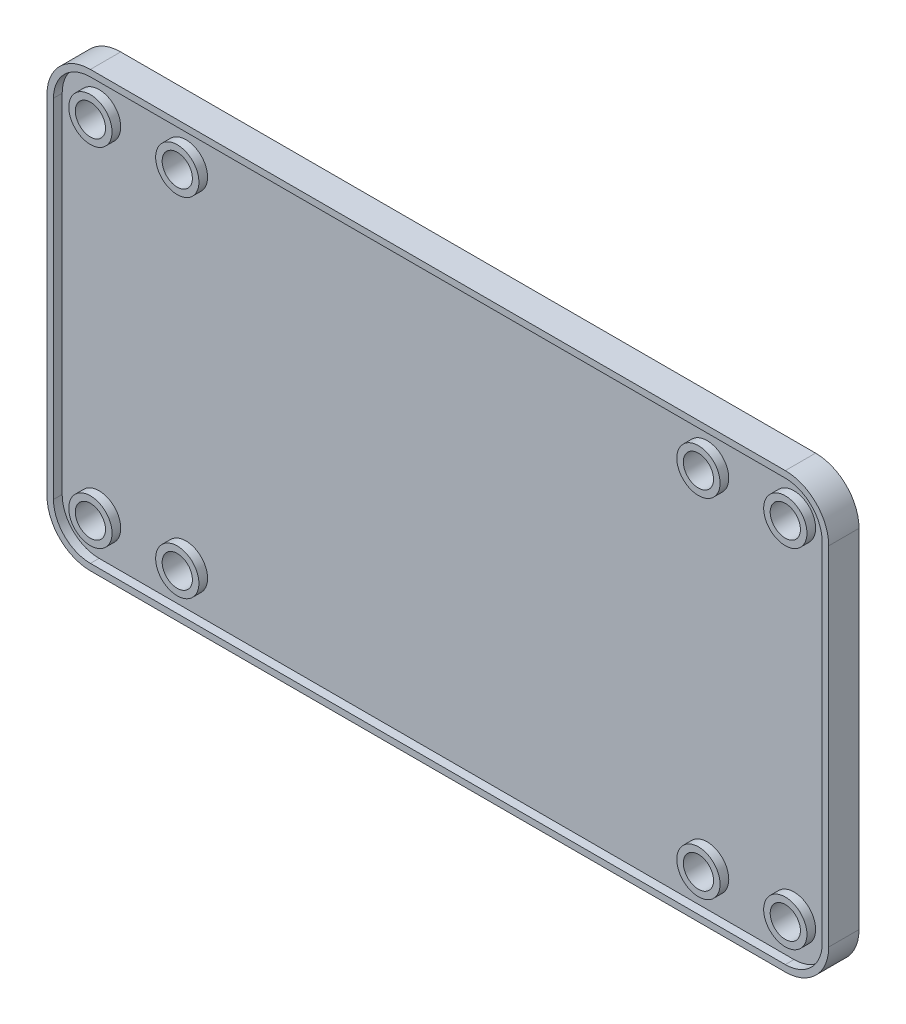
SolidWorks part; units mm, degrees
material "ABS"
ref_plane "Front Plane" through (0, 0, 0) normal (0, 0, 1) x (1, 0, 0)
ref_plane "Top Plane" through (0, 0, 0) normal (0, 1, 0) x (1, 0, 0)
ref_plane "Right Plane" through (0, 0, 0) normal (1, 0, 0) x (0, 0, -1)
sketch "Sketch1" plane through (0, 0, 0) normal (0, 0, 1) x (1, 0, 0)
  line L0 (-57.15, 0) -> (57.15, 0) construction
  line L1 (-50.8, -31.75) -> (50.8, -31.75)
  line L2 (-57.15, -25.4) -> (-57.15, 25.4)
  line L3 (-50.8, 31.75) -> (50.8, 31.75)
  line L4 (57.15, -25.4) -> (57.15, 25.4)
  line L5 (-57.15, -31.75) -> (57.15, 31.75) construction
  line L6 (-57.15, 31.75) -> (57.15, -31.75) construction
  line L7 (0, 31.75) -> (0, -31.75) construction
  arc A0 (50.8, 31.75) -> (57.15, 25.4) centre (50.8, 25.4) cw
  arc A1 (50.8, -31.75) -> (57.15, -25.4) centre (50.8, -25.4) ccw
  arc A2 (-50.8, -31.75) -> (-57.15, -25.4) centre (-50.8, -25.4) cw
  arc A3 (-57.15, 25.4) -> (-50.8, 31.75) centre (-50.8, 25.4) cw
  circle A4 centre (-50.8, -25.4) radius 2.2098
  circle A5 centre (-38.1, -25.4) radius 2.2098
  circle A6 centre (-50.8, 25.4) radius 2.2098
  circle A7 centre (-38.1, 25.4) radius 2.2098
  circle A8 centre (50.8, 25.4) radius 2.2098
  circle A9 centre (38.1, 25.4) radius 2.2098
  circle A10 centre (50.8, -25.4) radius 2.2098
  circle A11 centre (38.1, -25.4) radius 2.2098
  point P0 (0, 0)
  dimension "D3" = 6.35
  dimension "D4" = 4.4196
  dimension "D1" = 63.5
  dimension "D2" = 114.3
  dimension "D5" = 6.35
  dimension "D6" = 12.7
  dimension "D7" = 6.35
extrude "Boss-Extrude1" add sketch "Sketch1" against normal blind 3.175
sketch "Sketch2" plane through (0, 0, 0) normal (0, 0, 1) x (1, 0, 0)
  line L12 (50.8, 30.7975) -> (-50.8, 30.7975)
  line L13 (-56.1975, 25.4) -> (-56.1975, -25.4)
  line L14 (-50.8, -30.7975) -> (50.8, -30.7975)
  line L15 (56.1975, -25.4) -> (56.1975, 25.4)
  line L16 (50.8, 30.7975) -> (-50.8, 30.7975)
  line L17 (-56.1975, 25.4) -> (-56.1975, -25.4)
  line L18 (-50.8, -30.7975) -> (50.8, -30.7975)
  line L19 (56.1975, -25.4) -> (56.1975, 25.4)
  circle A0 centre (-50.8, -25.4) radius 2.2098 construction
  arc A8 (56.1975, 25.4) -> (50.8, 30.7975) centre (50.8, 25.4) ccw
  arc A9 (-50.8, 30.7975) -> (-56.1975, 25.4) centre (-50.8, 25.4) ccw
  arc A10 (-56.1975, -25.4) -> (-50.8, -30.7975) centre (-50.8, -25.4) ccw
  arc A11 (50.8, -30.7975) -> (56.1975, -25.4) centre (50.8, -25.4) ccw
  arc A12 (56.1975, 25.4) -> (50.8, 30.7975) centre (50.8, 25.4) ccw
  arc A13 (-50.8, 30.7975) -> (-56.1975, 25.4) centre (-50.8, 25.4) ccw
  arc A14 (-56.1975, -25.4) -> (-50.8, -30.7975) centre (-50.8, -25.4) ccw
  arc A15 (50.8, -30.7975) -> (56.1975, -25.4) centre (50.8, -25.4) ccw
  circle A36 centre (38.1, 25.4) radius 3.1623
  circle A37 centre (50.8, 25.4) radius 3.1623
  circle A38 centre (50.8, -25.4) radius 3.1623
  circle A39 centre (38.1, -25.4) radius 3.1623
  circle A40 centre (-38.1, -25.4) radius 3.1623
  circle A41 centre (-50.8, -25.4) radius 3.1623
  circle A42 centre (-38.1, 25.4) radius 3.1623
  circle A43 centre (-50.8, 25.4) radius 3.1623
  circle A44 centre (-38.1, -25.4) radius 2.2098 construction
  circle A47 centre (38.1, -25.4) radius 2.2098 construction
  circle A50 centre (50.8, -25.4) radius 2.2098 construction
  circle A51 centre (50.8, 25.4) radius 2.2098 construction
  circle A52 centre (38.1, 25.4) radius 2.2098 construction
  circle A53 centre (-38.1, 25.4) radius 2.2098 construction
  circle A54 centre (-50.8, 25.4) radius 2.2098 construction
  dimension "D2" = 0.9525
  dimension "D1" = 0.9525
extrude "Cut-Extrude3" cut sketch "Sketch2" against normal blind 1.27
sketch "Sketch3" plane through (0, 0, -3.175) normal (0, 0, -1) x (-1, 0, 0)
  line L4 (-57.15, 25.4) -> (-57.15, -25.4)
  line L5 (-50.8, -31.75) -> (50.8, -31.75)
  line L6 (57.15, -25.4) -> (57.15, 25.4)
  line L7 (50.8, 31.75) -> (-50.8, 31.75)
  line L8 (-57.15, 25.4) -> (-57.15, -25.4)
  line L9 (-50.8, -31.75) -> (50.8, -31.75)
  line L10 (57.15, -25.4) -> (57.15, 25.4)
  line L11 (50.8, 31.75) -> (-50.8, 31.75)
  circle A0 centre (-50.8, -25.4) radius 2.2098 construction
  circle A1 centre (-38.1, -25.4) radius 2.2098 construction
  circle A2 centre (38.1, -25.4) radius 2.2098 construction
  circle A3 centre (50.8, -25.4) radius 2.2098 construction
  arc A4 (-50.8, 31.75) -> (-57.15, 25.4) centre (-50.8, 25.4) ccw
  arc A5 (-57.15, -25.4) -> (-50.8, -31.75) centre (-50.8, -25.4) ccw
  arc A6 (50.8, -31.75) -> (57.15, -25.4) centre (50.8, -25.4) ccw
  arc A7 (57.15, 25.4) -> (50.8, 31.75) centre (50.8, 25.4) ccw
  arc A8 (-50.8, 31.75) -> (-57.15, 25.4) centre (-50.8, 25.4) ccw
  arc A9 (-57.15, -25.4) -> (-50.8, -31.75) centre (-50.8, -25.4) ccw
  arc A10 (50.8, -31.75) -> (57.15, -25.4) centre (50.8, -25.4) ccw
  arc A11 (57.15, 25.4) -> (50.8, 31.75) centre (50.8, 25.4) ccw
  circle A12 centre (50.8, 25.4) radius 2.2098 construction
  circle A13 centre (38.1, 25.4) radius 2.2098 construction
  circle A14 centre (-38.1, 25.4) radius 2.2098 construction
  circle A15 centre (-50.8, 25.4) radius 2.2098 construction
  circle A16 centre (-50.8, -25.4) radius 2.2098
  circle A17 centre (-38.1, -25.4) radius 2.2098
  circle A18 centre (38.1, -25.4) radius 2.2098
  circle A19 centre (50.8, -25.4) radius 2.2098
  circle A20 centre (50.8, 25.4) radius 2.2098
  circle A21 centre (38.1, 25.4) radius 2.2098
  circle A22 centre (-38.1, 25.4) radius 2.2098
  circle A23 centre (-50.8, 25.4) radius 2.2098
  dimension "D1" = 0
extrude "Boss-Extrude2" add sketch "Sketch3" along normal blind 1.253
equation "\"tolerance\"= 0.005"
equation "\"D4@Sketch1\"=0.164 + \"tolerance\" * 2"
equation "\"D1@Boss-Extrude2\"=1.38mm- \"tolerance\""
